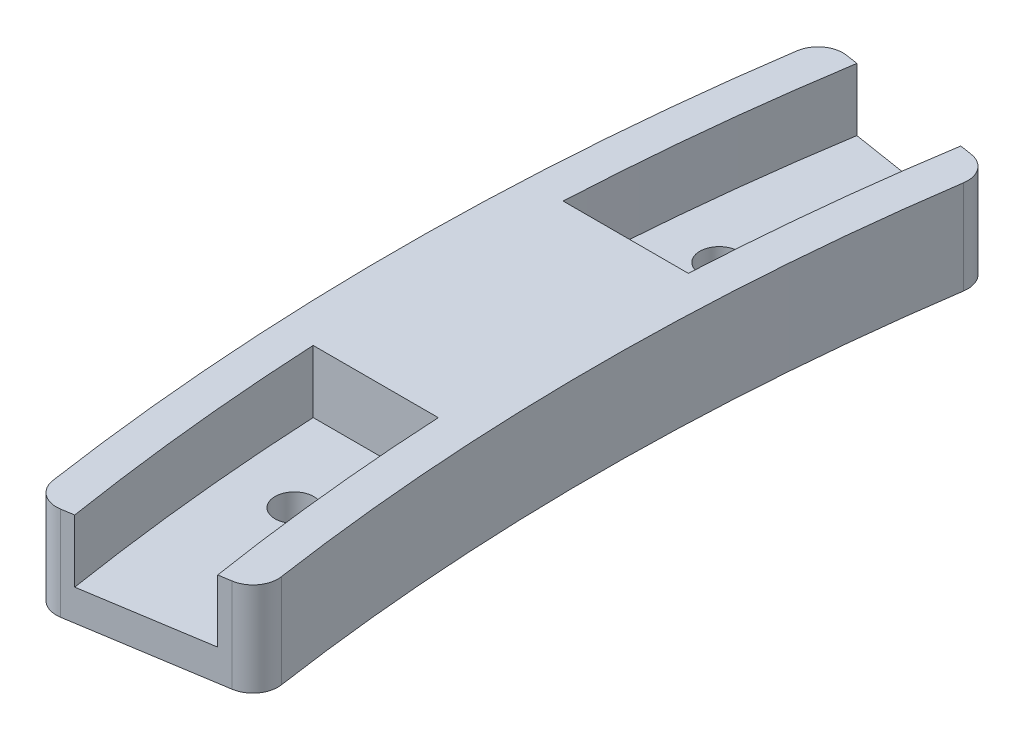
SolidWorks part; units mm, degrees
ref_plane "Front Plane" through (0, 0, 0) normal (0, 0, 1) x (1, 0, 0)
ref_plane "Top Plane" through (0, 0, 0) normal (0, 1, 0) x (1, 0, 0)
ref_plane "Right Plane" through (0, 0, 0) normal (1, 0, 0) x (0, 0, -1)
sketch "Sketch1" plane through (0, 0, 0) normal (0, 1, 0) x (1, 0, 0)
  line L0 (0, 0) -> (-197.5377, -31.2869) construction
  line L1 (0, 0) -> (-197.5377, 31.2869) construction
  line L2 (0, 0) -> (-195, 0) construction
  line L3 (-197.5377, 31.2869) -> (-187.6608, 29.7225)
  line L4 (-187.6608, -29.7225) -> (-197.5377, -31.2869)
  line L5 (0, 0) -> (-200.5007, -31.7562) construction
  line L6 (0, 0) -> (-200.5007, 31.7562) construction
  line L7 (-200.5007, 31.7562) -> (-184.6977, 29.2532)
  line L8 (-200.5007, -31.7562) -> (-184.6977, -29.2532)
  arc A0 (-197.5377, 31.2869) -> (-197.5377, -31.2869) centre (0, 0) ccw
  arc A1 (-187.6608, 29.7225) -> (-187.6608, -29.7225) centre (0, 0) ccw
  arc A2 (-192.5992, -30.5047) -> (-192.5992, 30.5047) centre (0, 0) cw construction
  arc A4 (-184.6977, 29.2532) -> (-184.6977, -29.2532) centre (0, 0) ccw
  arc A5 (-200.5007, 31.7562) -> (-200.5007, -31.7562) centre (0, 0) ccw
  dimension "D1" = 200
  dimension "D2" = 190
  dimension "D3" = 5
  dimension "D5" = 187
  dimension "D6" = 203
  dimension "D4" = 18
extrude "Boss-Extrude1" add sketch "Sketch1" along normal blind 10 contours A1 L3 A0 L4 | L7 A5 L8 A0 | A4 L7 A1 L8
ref_plane "Plane1" through (-195, 0, 0) normal (1, 0, 0) x (0, 0, -1)
sketch "Sketch15" plane through (0, 10, 0) normal (0, 1, 0) x (1, 0, 0)
  line L0 (-187.6608, -29.7225) -> (-197.5377, -31.2869) construction
  line L1 (-185, 10) -> (-205, 10)
  line L2 (-185, 10) -> (-185, -10)
  line L3 (-185, -10) -> (-205, -10)
  line L4 (-205, 10) -> (-205, -10)
  line L5 (-185, 10) -> (-205, -10) construction
  line L6 (-185, -10) -> (-205, 10) construction
  line L7 (-197.5377, 31.2869) -> (-187.6608, 29.7225) construction
  line L8 (-187.6608, -29.7225) -> (-197.5377, -31.2869)
  line L9 (-197.5377, 31.2869) -> (-187.6608, 29.7225)
  arc A2 (-187.6608, 29.7225) -> (-187.6608, -29.7225) centre (0, 0) ccw construction
  arc A3 (-197.5377, 31.2869) -> (-197.5377, -31.2869) centre (0, 0) ccw construction
  arc A4 (-187.6608, 29.7225) -> (-187.6608, -29.7225) centre (0, 0) ccw
  arc A5 (-197.5377, 31.2869) -> (-197.5377, -31.2869) centre (0, 0) ccw
  point P0 (-195, 0)
  line M5 (-200.5007, -31.7562) -> (-184.6977, -29.2532)
  line M7 (-184.6977, 29.2532) -> (-200.5007, 31.7562)
  dimension "D1" = 20
  dimension "D2" = 20
extrude "Cut-Extrude1" cut sketch "Sketch15" against normal blind 5 contours A5 L1 A4 M7 | L3 A5 A4 M5
ref_plane "Plane2" through (-195, 0, 0) normal (-1, 0, 0) x (0, 0, 1)
sketch "Sketch12" plane through (0, 0, 0) normal (0, 1, 0) x (1, 0, 0)
  line L0 (0, 0) -> (-194.258, -16.9954) construction
  line L1 (0, 0) -> (-193.3317, -25.4526) construction
  line L2 (0, 0) -> (-195, 0) construction
  line L3 (0, 0) -> (-195, 0) construction
  line L4 (0, 0) -> (-194.258, 16.9954) construction
  line L5 (0, 0) -> (-193.3317, 25.4526) construction
  arc A0 (-192.5992, 30.5047) -> (-192.5992, -30.5047) centre (0, 0) ccw construction
  point P11 (0, 0)
  dimension "D1" = 10
  dimension "D2" = 15
fillet "Fillet1" radius 2 4 edges at (-200.5007, 5, -31.7562) (-184.6977, 5, -29.2532) (-200.5007, 5, 31.7562) (-184.6977, 5, 29.2532)
sketch "Sketch19" plane through (0, 0, 0) normal (0, -1, 0) x (1, 0, 0)
  line L2 (-198.5155, -31.4418) -> (-186.6626, -29.5645)
  line L3 (-186.6626, 29.5645) -> (-198.5155, 31.4418)
  line L4 (-198.5155, -31.4418) -> (-186.6626, -29.5645)
  line L5 (-186.6626, 29.5645) -> (-198.5155, 31.4418)
  arc A6 (-200.8068, 29.7596) -> (-200.8068, -29.7596) centre (0, 0) ccw
  arc A7 (-200.8068, -29.7596) -> (-198.5155, -31.4418) centre (-198.8284, -29.4664) ccw
  arc A8 (-186.6626, -29.5645) -> (-184.9969, -27.2971) centre (-186.9755, -27.5891) ccw
  arc A9 (-184.9969, 27.2971) -> (-184.9969, -27.2971) centre (0, 0) ccw
  arc A10 (-184.9969, 27.2971) -> (-186.6626, 29.5645) centre (-186.9755, 27.5891) ccw
  arc A11 (-198.5155, 31.4418) -> (-200.8068, 29.7596) centre (-198.8284, 29.4664) ccw
  arc A12 (-200.8068, 29.7596) -> (-200.8068, -29.7596) centre (0, 0) ccw
  arc A13 (-200.8068, -29.7596) -> (-198.5155, -31.4418) centre (-198.8284, -29.4664) ccw
  arc A14 (-186.6626, -29.5645) -> (-184.9969, -27.2971) centre (-186.9755, -27.5891) ccw
  arc A15 (-184.9969, 27.2971) -> (-184.9969, -27.2971) centre (0, 0) ccw
  arc A16 (-184.9969, 27.2971) -> (-186.6626, 29.5645) centre (-186.9755, 27.5891) ccw
  arc A17 (-198.5155, 31.4418) -> (-200.8068, 29.7596) centre (-198.8284, 29.4664) ccw
  dimension "D1" = 0
extrude "Cut-Extrude2" cut sketch "Sketch19" against normal blind 2.5
hole_wizard "Ø3.1 (3.1) Diameter Hole1" positions "Sketch20" profile "Sketch21" hole size "Ø3.1" standard "ISO" end condition through all
sketch "Sketch20" plane through (0, 2.5, 0) normal (0, -1, 0) x (-1, 0, 0)
  point P0 (194.258, 16.9954)
  point P3 (194.258, -16.9954)
sketch "Sketch21" plane through (-194.258, 2.5, -16.9954) normal (1, 0, 0) x (0, 0, -1)
  line L0 (0, 0) -> (0, 7.5)
  line L1 (0, 7.5) -> (1.55, 7.5)
  line L2 (1.55, 7.5) -> (1.55, 0)
  line L5 (1.55, 0) -> (0, 0)
  line L11 (0, -6.35) -> (0, 107.95) construction
  dimension "Thru Hole Dia." = 3.1
  dimension "Thru Hole Depth" = 7.5
